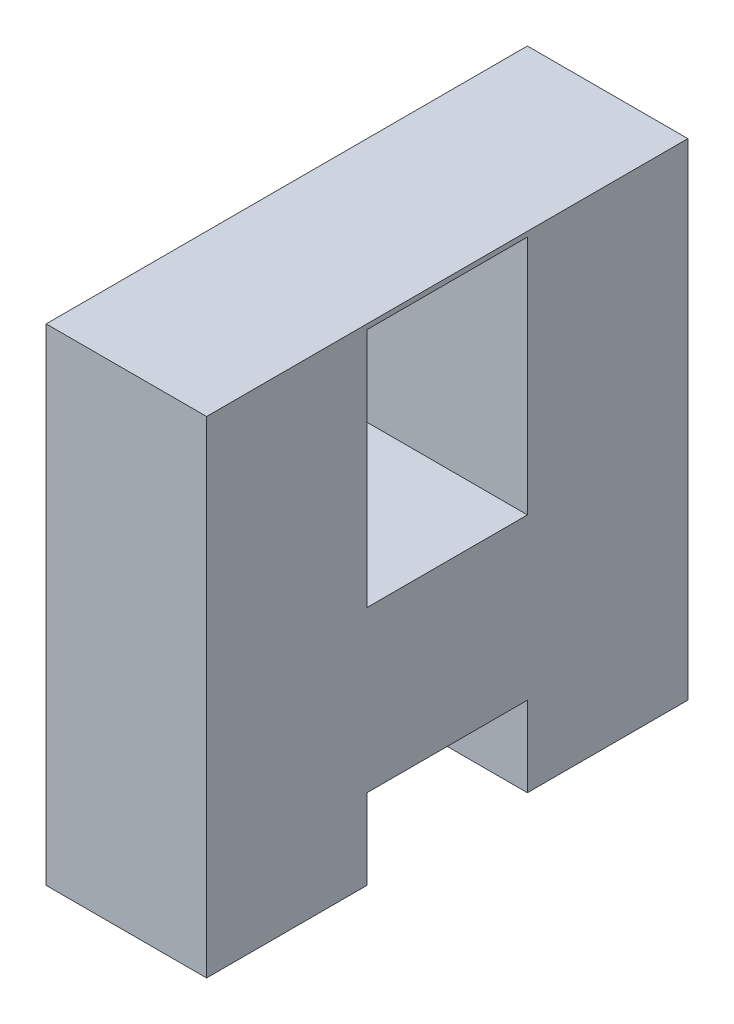
SolidWorks part; units mm, degrees
ref_plane "Front Plane" through (0, 0, 0) normal (0, 0, 1) x (1, 0, 0)
ref_plane "Top Plane" through (0, 0, 0) normal (0, 1, 0) x (1, 0, 0)
ref_plane "Right Plane" through (0, 0, 0) normal (1, 0, 0) x (0, 0, -1)
sketch "Sketch2" plane through (0, 0, 0) normal (1, 0, 0) x (0, 0, -1)
  line L1 (0, 0) -> (304.8, 0)
  line L2 (0, 0) -> (0, 307.975)
  line L3 (0, 307.975) -> (304.8, 307.975)
  line L4 (304.8, 0) -> (304.8, 307.975)
  line L5 (101.6, 0) -> (203.2, 0)
  line L6 (101.6, 0) -> (101.6, 50.8)
  line L7 (101.6, 50.8) -> (203.2, 50.8)
  line L8 (203.2, 0) -> (203.2, 50.8)
  line L9 (101.6, 152.4) -> (203.2, 152.4)
  line L10 (101.6, 152.4) -> (101.6, 304.8)
  line L11 (101.6, 304.8) -> (203.2, 304.8)
  line L12 (203.2, 152.4) -> (203.2, 304.8)
  dimension "D1" = 307.975
  dimension "D2" = 304.8
  dimension "D3" = 50.8
  dimension "D4" = 101.6
  dimension "D5" = 101.6
  dimension "D6" = 101.6
  dimension "D7" = 101.6
  dimension "D8" = 152.4
  dimension "D9" = 101.6
extrude "Boss-Extrude1" add sketch "Sketch2" along normal blind 101.6 contours L8 L1 L4 L3 L2 L6 L7 L12 L9 L10 L11
